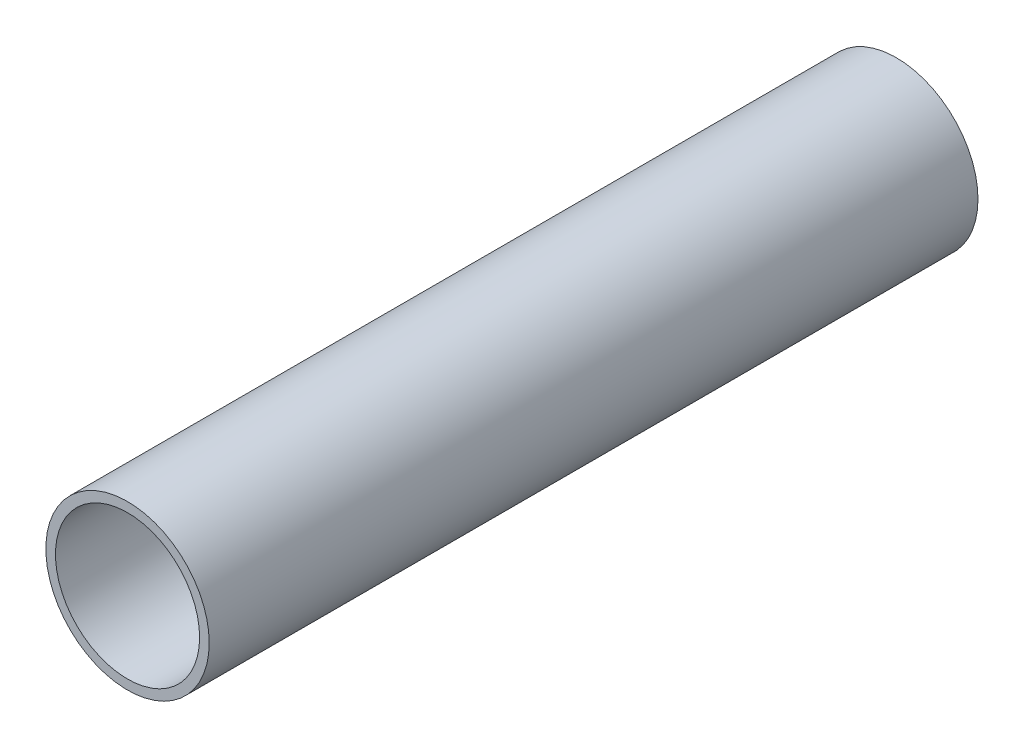
SolidWorks part; units mm, degrees
ref_plane "Front Plane" through (0, 0, 0) normal (0, 0, 1) x (1, 0, 0)
ref_plane "Top Plane" through (0, 0, 0) normal (0, 1, 0) x (1, 0, 0)
ref_plane "Right Plane" through (0, 0, 0) normal (1, 0, 0) x (0, 0, -1)
sketch "Sketch1" plane through (0, 0, 0) normal (0, 0, 1) x (1, 0, 0)
  circle A0 centre (0, 0) radius 15
  circle A1 centre (0, 0) radius 17
  dimension "D1" = 30
  dimension "D2" = 2
extrude "Boss-Extrude1" add sketch "Sketch1" along normal mid plane 160 contours A1 A0
